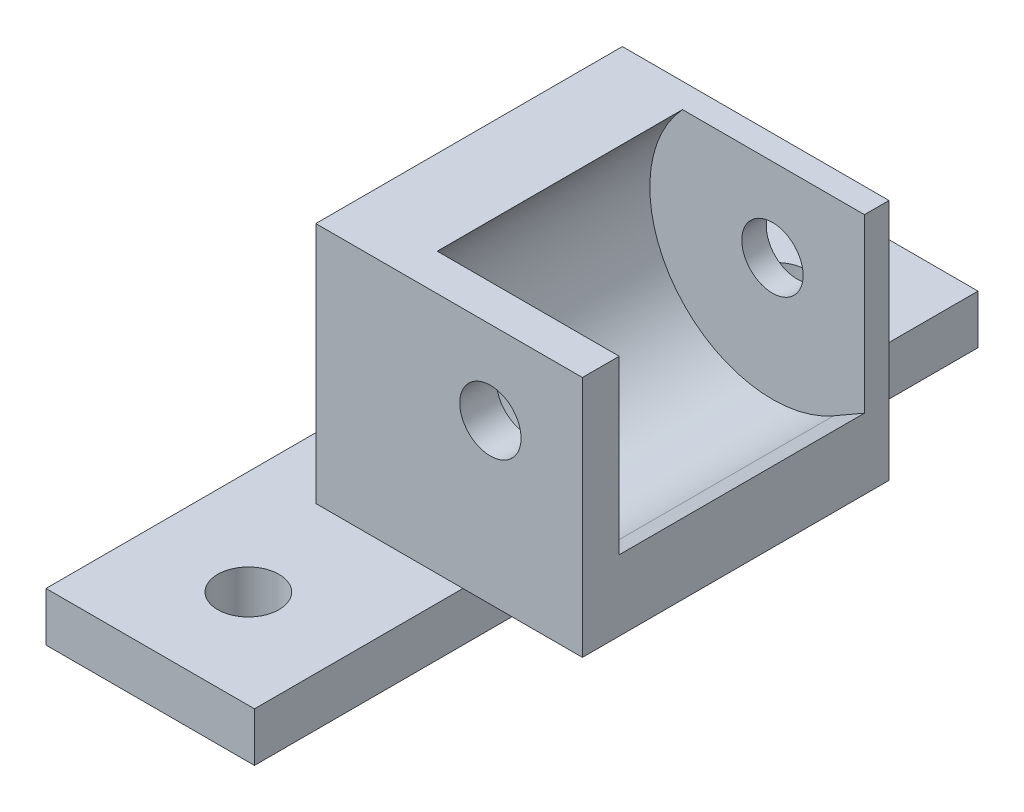
SolidWorks part; units mm, degrees
ref_plane "Front Plane" through (0, 0, 0) normal (0, 0, 1) x (1, 0, 0)
ref_plane "Top Plane" through (0, 0, 0) normal (0, 1, 0) x (1, 0, 0)
ref_plane "Right Plane" through (0, 0, 0) normal (1, 0, 0) x (0, 0, -1)
sketch "Sketch1" plane through (0, 0, 0) normal (0, 0, 1) x (1, 0, 0)
  line L0 (-527.7276, 348.6336) -> (-500.1158, 348.6336)
  line L1 (-500.1158, 348.6336) -> (-500.1158, 323.526)
  line L2 (-500.1158, 323.526) -> (-527.7276, 323.526)
  line L3 (-527.7276, 323.526) -> (-527.7276, 348.6336)
  line L4 (-471.0414, 347.5416) -> (-503.3159, 328.9895) construction
  line L5 (-471.0414, 347.5416) -> (-503.3159, 328.9895)
  arc A0 (-508.6898, 327.336) -> (-503.3159, 328.9895) centre (-509.645, 340) ccw construction
  arc A1 (-515.9742, 351.0105) -> (-520.1076, 347.199) centre (-509.645, 340) ccw construction
  arc A2 (-520.1076, 347.199) -> (-508.6898, 327.336) centre (-509.645, 340) ccw construction
  arc A3 (-508.6898, 327.336) -> (-503.3159, 328.9895) centre (-509.645, 340) ccw
  arc A4 (-515.9742, 351.0105) -> (-520.1076, 347.199) centre (-509.645, 340) ccw
  arc A5 (-520.1076, 347.199) -> (-508.6898, 327.336) centre (-509.645, 340) ccw
  dimension "D1" = 3.81
  dimension "D2" = 7.62
  dimension "D3" = 25.1076
  dimension "D4" = 27.6118
extrude "Boss-Extrude1" add sketch "Sketch1" against normal blind 27.94 contours A5 A4 L0 L3 L2 L1 L5 A3
sketch "Sketch2" plane through (0, 0, -25.4) normal (0, 0, -1) x (-1, 0, 0)
  line L0 (500.1158, 330.829) -> (500.1158, 348.6336)
  line L1 (500.1158, 348.6336) -> (518.9591, 348.6336)
  line L2 (500.1158, 330.829) -> (503.3159, 328.9895) construction
  line L3 (500.1158, 330.829) -> (503.3159, 328.9895)
  arc A0 (503.3159, 328.9895) -> (518.9591, 348.6336) centre (509.645, 340) ccw construction
  arc A1 (503.3159, 328.9895) -> (518.9591, 348.6336) centre (509.645, 340) ccw
  circle A2 centre (509.645, 340) radius 3.175
  dimension "D1" = 6.35
extrude "Boss-Extrude2" add sketch "Sketch2" along normal up to surface (2.54 mm away) up to face at (-514.4007, 332.9024, -27.94)
sketch "Sketch3" plane through (0, 0, 0) normal (0, 0, 1) x (1, 0, 0)
  line L0 (-527.7276, 348.6336) -> (-500.1158, 348.6336)
  line L1 (-500.1158, 348.6336) -> (-500.1158, 323.526)
  line L2 (-500.1158, 323.526) -> (-527.7276, 323.526)
  line L3 (-527.7276, 323.526) -> (-527.7276, 348.6336)
  circle A0 centre (-509.645, 340) radius 3.175
  dimension "D1" = 6.35
extrude "Boss-Extrude3" add sketch "Sketch3" along normal blind 3.81 contours L3 L0 L1 L2 | A0
ref_plane "Plane1" through (0, 323.526, 0) normal (0, 1, 0) x (1, 0, 0)
sketch "Sketch4" plane through (0, 323.526, 0) normal (0, 1, 0) x (1, 0, 0)
  line L0 (-527.7276, 27.94) -> (-527.7276, -3.81) construction
  line L1 (-534.0776, 49.53) -> (-512.4876, 49.53)
  line L2 (-534.0776, 49.53) -> (-534.0776, -25.4)
  line L3 (-534.0776, -25.4) -> (-512.4876, -25.4)
  line L4 (-512.4876, 49.53) -> (-512.4876, -25.4)
  line L5 (-527.7276, 27.94) -> (-500.1158, 27.94) construction
  line L6 (-527.7276, -3.81) -> (-500.1158, -3.81) construction
  circle A0 centre (-523.2826, -15.24) radius 3.175
  circle A1 centre (-523.2826, 39.37) radius 3.175
  dimension "D5" = 10.16
  dimension "D9" = 6.35
  dimension "D10" = 6.35
  dimension "D1" = 6.35
  dimension "D2" = 21.59
  dimension "D3" = 21.59
  dimension "D4" = 21.59
  dimension "D6" = 10.795
  dimension "D7" = 10.16
  dimension "D8" = 10.795
extrude "Boss-Extrude4" add sketch "Sketch4" against normal blind 5.08
